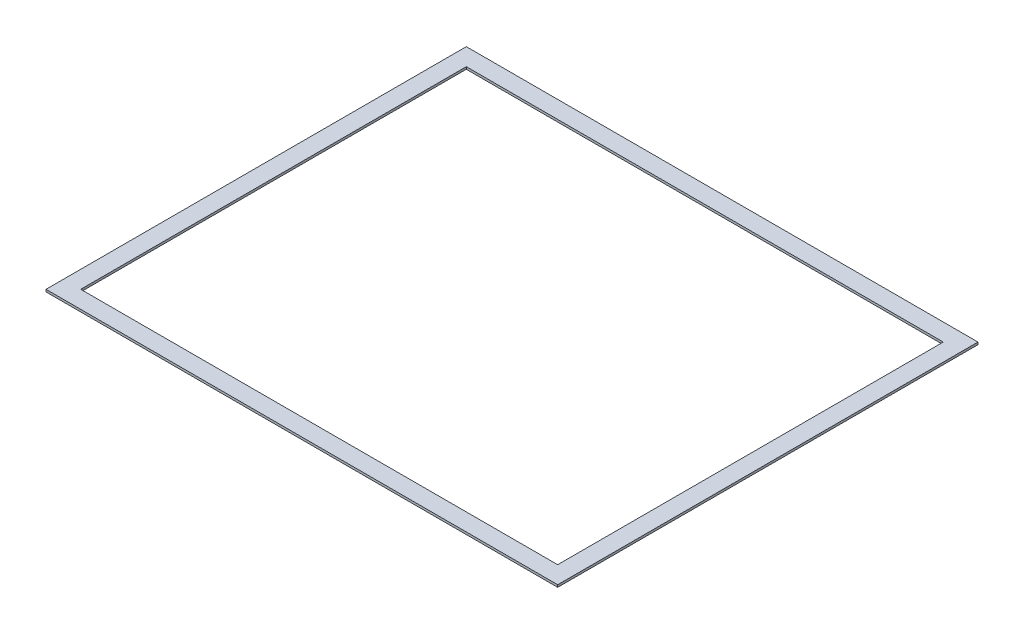
SolidWorks part; units mm, degrees
ref_plane "Front Plane" through (0, 0, 0) normal (0, 0, 1) x (1, 0, 0)
ref_plane "Top Plane" through (0, 0, 0) normal (0, 1, 0) x (1, 0, 0)
ref_plane "Right Plane" through (0, 0, 0) normal (1, 0, 0) x (0, 0, -1)
sketch "Sketch1" plane through (0, 0, 0) normal (0, 1, 0) x (1, 0, 0)
  line L1 (0, 0) -> (-280, 0)
  line L2 (0, 0) -> (0, 230)
  line L3 (0, 230) -> (-280, 230)
  line L4 (-280, 0) -> (-280, 230)
  dimension "D1" = 280
  dimension "D2" = 230
extrude "Boss-Extrude1" add sketch "Sketch1" along normal blind 1.25
sketch "Sketch2" plane through (0, 1.25, 0) normal (0, 1, 0) x (1, 0, 0)
  line L0 (-140, 230) -> (-140, 220.5) construction
  line L1 (0, 230) -> (-280, 230) construction
  line L2 (0, 220.5) -> (-9.5, 220.5) construction
  line L3 (0, 0) -> (0, 230) construction
  line L4 (-140, 0) -> (-140, 9.5) construction
  line L5 (-280, 0) -> (0, 0) construction
  line L6 (-280, 9.5) -> (-270.5, 9.5) construction
  line L7 (-280, 230) -> (-280, 0) construction
  line L9 (-270.5, 9.5) -> (-9.5, 9.5)
  line L10 (-270.5, 9.5) -> (-270.5, 220.5)
  line L11 (-270.5, 220.5) -> (-9.5, 220.5)
  line L12 (-9.5, 9.5) -> (-9.5, 220.5)
  dimension "D1" = 9.5
  dimension "D2" = 9.5
  dimension "D3" = 9.5
  dimension "D4" = 9.5
extrude "Cut-Extrude1" cut sketch "Sketch2" against normal through all
